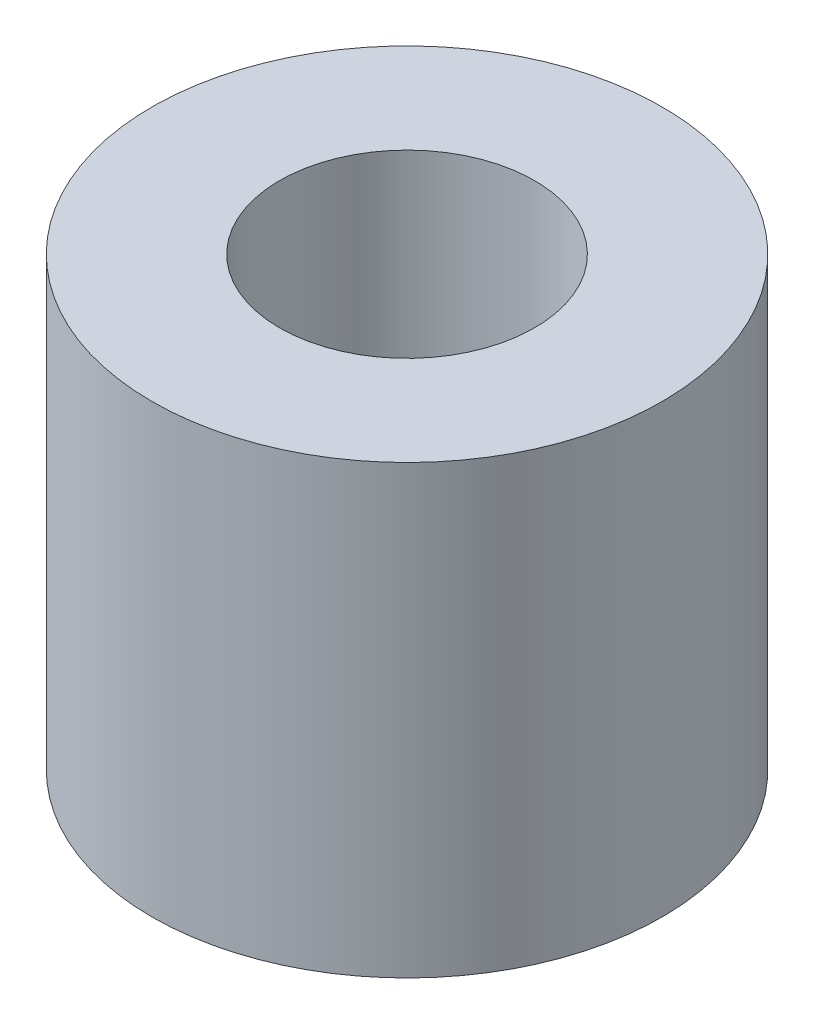
SolidWorks part; units mm, degrees
ref_plane "Front Plane" through (0, 0, 0) normal (0, 0, 1) x (1, 0, 0)
ref_plane "Top Plane" through (0, 0, 0) normal (0, 1, 0) x (1, 0, 0)
ref_plane "Right Plane" through (0, 0, 0) normal (1, 0, 0) x (0, 0, -1)
sketch "Sketch1" plane through (0, 0, 0) normal (0, 1, 0) x (1, 0, 0)
  circle A0 centre (0, 0) radius 2
  circle A1 centre (0, 0) radius 1
  dimension "D1" = 4
  dimension "D2" = 2
extrude "Boss-Extrude1" add sketch "Sketch1" along normal blind 3.5
